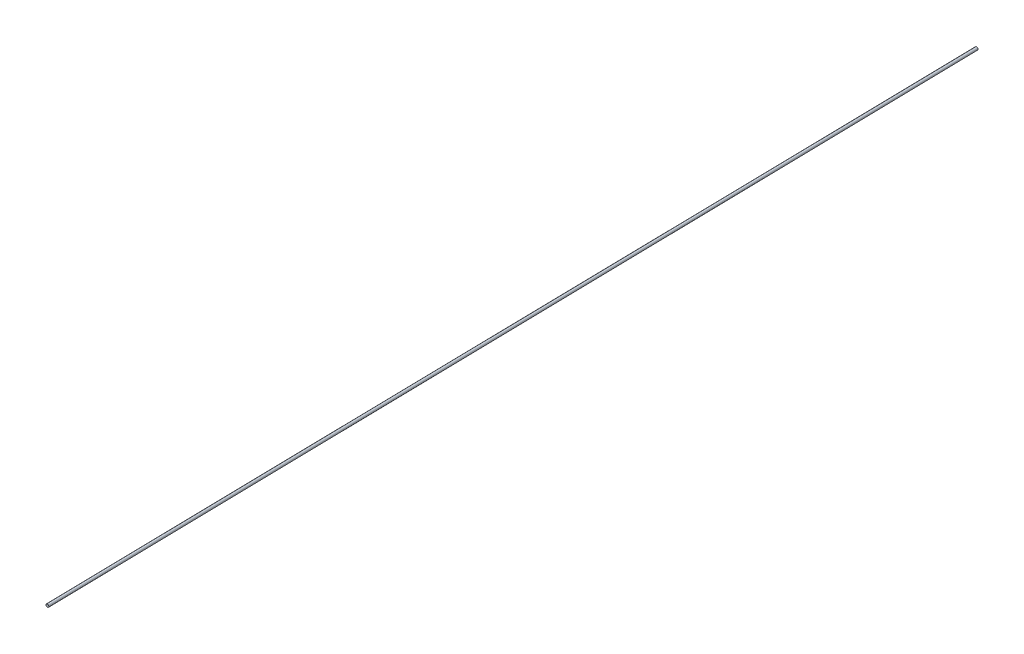
SolidWorks part; units mm, degrees
ref_plane "Alzado" through (0, 0, 0) normal (0, 0, 1) x (1, 0, 0)
ref_plane "Planta" through (0, 0, 0) normal (0, 1, 0) x (1, 0, 0)
ref_plane "Vista lateral" through (0, 0, 0) normal (1, 0, 0) x (0, 0, -1)
sketch "Croquis3" plane through (0, 0, 0) normal (1, 0, 0) x (0, 0, -1)
  line L0 (0, 0) -> (772.1351, -7.8789) construction
  line L1 (0, 0) -> (977.337, 18.9124)
  point P1 (870.9528, 31.4373)
  point P4 (971.5013, 6.0205)
  point P5 (0, 0)
  point P6 (870.12, 52.0201)
  point P8 (192.2351, 3.7199)
  point P9 (971.3382, 18.7963)
  dimension "D1" = 977.52
sweep "Barrer1" add path "Croquis3" circular profile diameter 3 parameters "D3"=3
sketch "Croquis13" plane through (0, 18.9124, -977.337) normal (0, 0.0193, -0.9998) x (-1, 0, 0)
  line L0 (0, 0) -> (0, -5.7272) construction
  point P4 (0, -5.7272)
sketch "Croquis14" plane through (0, 0, 0) normal (0, -0.0193, 0.9998) x (1, 0, 0)
  line L0 (0, 0) -> (0, -6.1912) construction
  point P4 (0, -6.1912)
